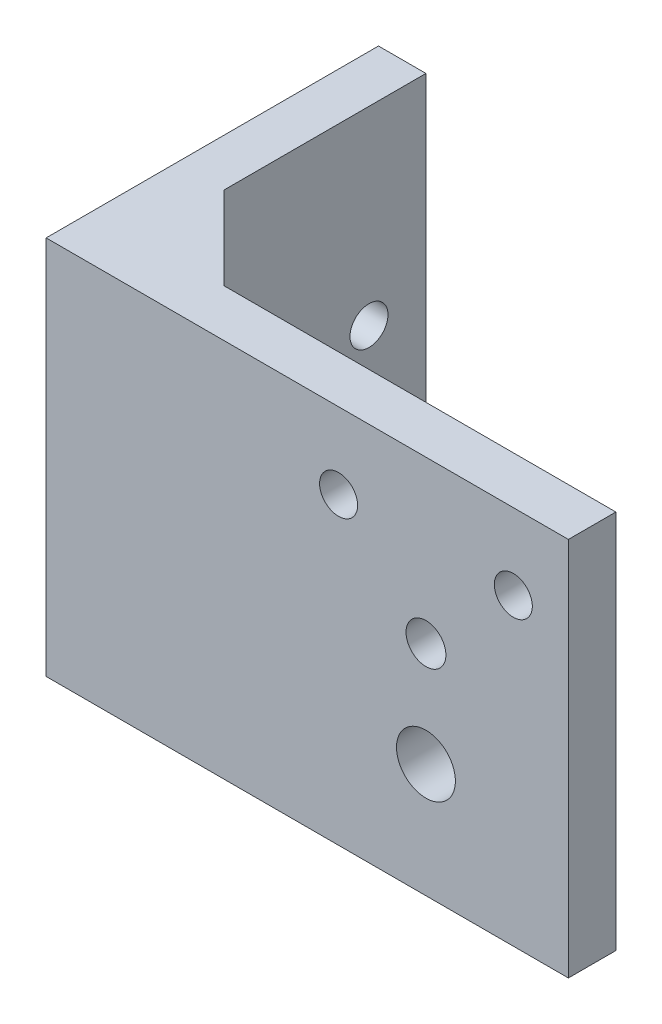
SolidWorks part; units mm, degrees
ref_plane "Front Plane" through (0, 0, 0) normal (0, 0, 1) x (1, 0, 0)
ref_plane "Top Plane" through (0, 0, 0) normal (0, 1, 0) x (1, 0, 0)
ref_plane "Right Plane" through (0, 0, 0) normal (1, 0, 0) x (0, 0, -1)
sketch "Sketch1" plane through (0, 0, 0) normal (0, 1, 0) x (1, 0, 0)
  line L0 (0, 0) -> (55, 0)
  line L1 (55, 0) -> (55, 5)
  line L4 (5, 35) -> (0, 35)
  line L5 (0, 35) -> (0, 0)
  line L6 (5, 35) -> (5, 13.75)
  line L11 (5, 13.75) -> (13.75, 5)
  line L12 (13.75, 5) -> (55, 5)
  dimension "D1" = 35
  dimension "D2" = 55
  dimension "D3" = 5
  dimension "D4" = 5
extrude "Boss-Extrude3" add sketch "Sketch1" along normal blind 40 contours L12 L1 L0 L5 L4 L6 L11
sketch "Sketch5" plane through (0, 0, 0) normal (0, -1, 0) x (1, 0, 0)
  line L0 (5, -13.75) -> (5, -5)
  line L1 (5, -5) -> (13.75, -5)
  line L2 (13.75, -5) -> (5, -13.75)
extrude "Cut-Extrude1" cut sketch "Sketch5" against normal blind 35 contours L2 L0 L1
sketch "Sketch6" plane through (0, 0, 0) normal (0, -1, 0) x (1, 0, 0)
  line L0 (13.75, -5) -> (5, -13.75)
  line L1 (5, -13.75) -> (5, -5)
  line L2 (5, -5) -> (13.75, -5)
extrude "Boss-Extrude4" add sketch "Sketch6" against normal blind 5 contours L2 L0 L1
sketch "Sketch7" plane through (0, 0, -5) normal (0, 0, -1) x (-1, 0, 0)
  line L0 (-13.75, 0) -> (-55, 0) construction
  line L1 (-55, 40) -> (-55, 0) construction
  line L2 (-55, 40) -> (-40, 40)
  line L3 (-13.75, 40) -> (-55, 40) construction
  circle A0 centre (-40, 12) radius 3.1
  circle A1 centre (-40, 23) radius 2.1
  circle A2 centre (-49.2, 32) radius 2
  circle A3 centre (-30.8, 32) radius 2
  point P13 (0, 0)
  point P18 (0, 0)
  dimension "D1" = 18.4
  dimension "D5" = 8
  dimension "D6" = 15
  dimension "D3" = 12
  dimension "D4" = 5.8
extrude "Cut-Extrude7" cut sketch "Sketch7" against normal blind 5 contours A2 | A0 | A1 | A3
sketch "Sketch15" plane through (5, 0, 0) normal (1, 0, 0) x (0, 0, -1)
  line L0 (35, 40) -> (35, 0) construction
  line L1 (5, 35) -> (5, 5) construction
  line L2 (13.75, 40) -> (5, 40) construction
  circle A0 centre (11, 31) radius 2
  circle A1 centre (11, 9) radius 2
  circle A2 centre (29, 20) radius 2
  dimension "D1" = 6
  dimension "D2" = 9
  dimension "D3" = 22
  dimension "D4" = 6
extrude "Cut-Extrude8" cut sketch "Sketch15" against normal through all
